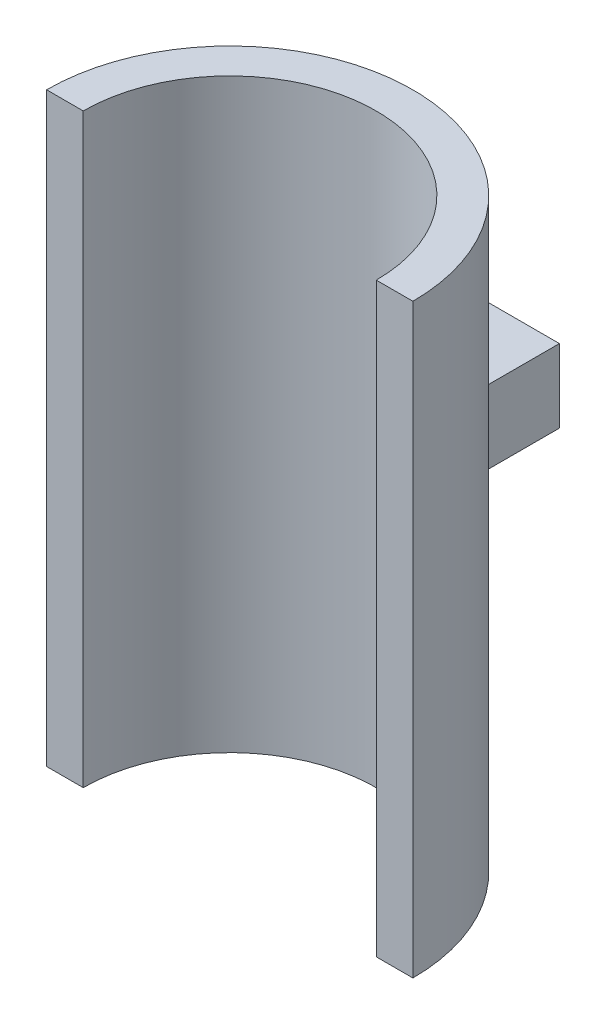
SolidWorks part; units mm, degrees
ref_plane "Plan de face" through (0, 0, 0) normal (0, 0, 1) x (1, 0, 0)
ref_plane "Plan de dessus" through (0, 0, 0) normal (0, 1, 0) x (1, 0, 0)
ref_plane "Plan de droite" through (0, 0, 0) normal (1, 0, 0) x (0, 0, -1)
sketch "Esquisse3" plane through (0, 7.6597, 0) normal (0, 1, 0) x (-1, 0, 0)
  line L0 (-4, 0) -> (-5, 0)
  line L1 (5, 0) -> (4, 0)
  arc A0 (-5, 0) -> (5, 0) centre (0, 0) ccw
  arc A2 (-4, 0) -> (4, 0) centre (0, 0) ccw
  dimension "D1" = 4
  dimension "D2" = 5
extrude "Boss.-Extru.3" add sketch "Esquisse3" along normal blind 16
ref_plane "Plan1" through (0, 0, -8) normal (0, 0, 1) x (1, 0, 0)
sketch "Esquisse4" plane through (0, 0, -8) normal (0, 0, 1) x (1, 0, 0)
  line L0 (-5, 23.6597) -> (-5, 7.6597) construction
  line L1 (-1, 14.6597) -> (1, 14.6597)
  line L2 (-1, 14.6597) -> (-1, 16.6597)
  line L3 (-1, 16.6597) -> (1, 16.6597)
  line L4 (1, 14.6597) -> (1, 16.6597)
  line L5 (-1, 14.6597) -> (1, 16.6597) construction
  line L6 (-1, 16.6597) -> (1, 14.6597) construction
  line L7 (4, 23.6597) -> (-4, 23.6597) construction
  point P0 (0, 15.6597)
  dimension "D1" = 2
  dimension "D2" = 2
  dimension "D3" = 4
  dimension "D4" = 7
extrude "Boss.-Extru.4" add sketch "Esquisse4" along normal up to next
